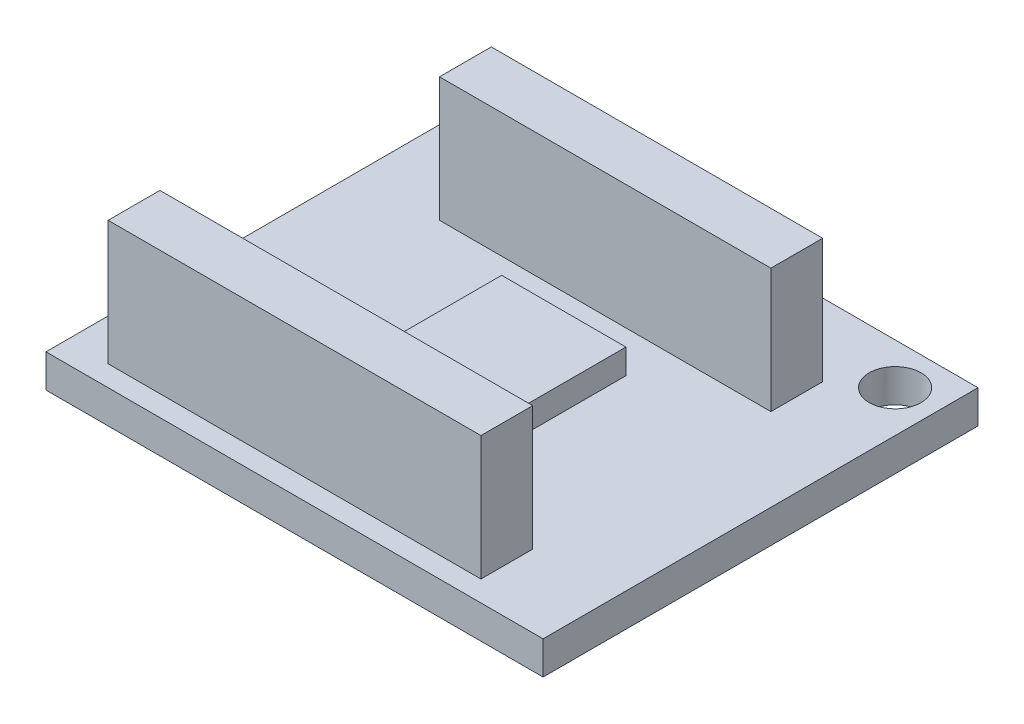
SolidWorks part; units mm, degrees
ref_plane "Front Plane" through (0, 0, 0) normal (0, 0, 1) x (1, 0, 0)
ref_plane "Top Plane" through (0, 0, 0) normal (0, 1, 0) x (1, 0, 0)
ref_plane "Right Plane" through (0, 0, 0) normal (1, 0, 0) x (0, 0, -1)
other "Configuration Table"
sketch "Sketch1" plane through (0, 0, 0) normal (0, 1, 0) x (1, 0, 0)
  line L1 (0, 0) -> (24, 0)
  line L2 (0, 0) -> (0, 21)
  line L3 (0, 21) -> (24, 21)
  line L4 (24, 0) -> (24, 21)
extrude "PCB" add sketch "Sketch1" along normal blind 1.6
sketch "Sketch2" plane through (0, 0, 0) normal (0, 1, 0) x (1, 0, 0)
  circle A0 centre (2, 19) radius 1.25
extrude "Mount_hole_1" cut sketch "Sketch2" against normal through all and the other way through all
sketch "Sketch3" plane through (0, 0, 0) normal (0, 1, 0) x (1, 0, 0)
  circle A0 centre (22, 19) radius 1.25
extrude "Mount_hole_2" cut sketch "Sketch3" against normal through all and the other way through all
sketch "Sketch4" plane through (0, 0, 0) normal (0, 1, 0) x (1, 0, 0)
  line L1 (9, 8) -> (15, 8)
  line L2 (9, 8) -> (9, 13)
  line L3 (9, 13) -> (15, 13)
  line L4 (15, 8) -> (15, 13)
extrude "MX1508_IC" add sketch "Sketch4" along normal blind 1.2 from offset 1.6
sketch "Sketch5" plane through (0, 0, 0) normal (0, 1, 0) x (1, 0, 0)
  line L1 (2, 1) -> (20, 1)
  line L2 (2, 1) -> (2, 3.5)
  line L3 (2, 3.5) -> (20, 3.5)
  line L4 (20, 1) -> (20, 3.5)
extrude "Pins_in" add sketch "Sketch5" along normal blind 6 from offset 1.6
sketch "Sketch6" plane through (0, 0, 0) normal (0, 1, 0) x (1, 0, 0)
  line L1 (4, 15) -> (20, 15)
  line L2 (4, 15) -> (4, 17.5)
  line L3 (4, 17.5) -> (20, 17.5)
  line L4 (20, 15) -> (20, 17.5)
extrude "Pins_out" add sketch "Sketch6" along normal blind 6 from offset 1.6
